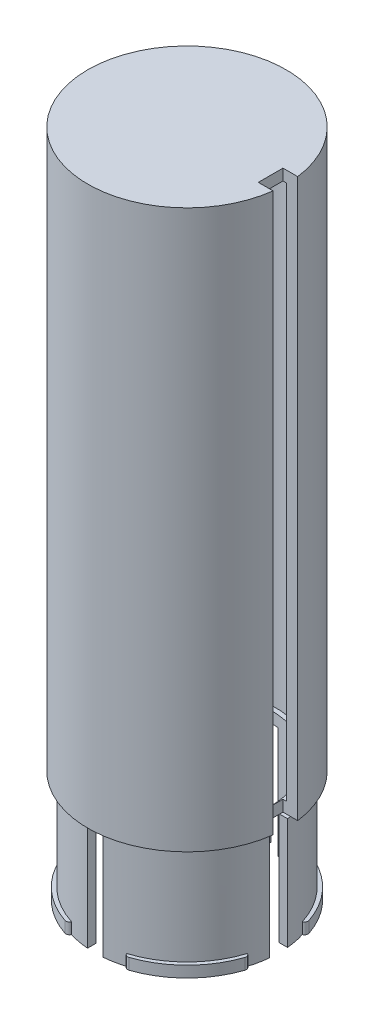
SolidWorks part; units mm, degrees
ref_plane "Front Plane" through (0, 0, 0) normal (0, 0, 1) x (1, 0, 0)
ref_plane "Top Plane" through (0, 0, 0) normal (0, 1, 0) x (1, 0, 0)
ref_plane "Right Plane" through (0, 0, 0) normal (1, 0, 0) x (0, 0, -1)
sketch "Sketch1" plane through (0, 0, 0) normal (0, 1, 0) x (1, 0, 0)
  line L5 (12.5724, 12.5724) -> (-12.5724, -12.5724) construction
  line L6 (12.5724, -12.5724) -> (-12.5724, 12.5724) construction
  circle A0 centre (0, 0) radius 17.78
  point P0 (0, 0)
  dimension "D1" = 35.56
extrude "Boss-Extrude1" add sketch "Sketch1" along normal blind 100
shell "Shell1" thickness 2
sketch "Sketch2" plane through (0, 0, 0) normal (1, 0, 0) x (0, 0, -1)
  line L0 (0, 19.558) -> (0, -19.558) construction
  line L1 (2.214, 104.2698) -> (-2.214, 104.2698)
  line L2 (2.214, 104.2698) -> (2.214, 0)
  line L3 (2.214, 0) -> (-2.214, 0)
  line L4 (-2.214, 104.2698) -> (-2.214, 0)
  line L5 (2.214, 104.2698) -> (-2.214, 0) construction
  line L6 (2.214, 0) -> (-2.214, 104.2698) construction
  line L7 (19.558, 0) -> (-19.558, 0) construction
  point P0 (0, 52.1349)
extrude "Cut-Extrude1" cut sketch "Sketch2" against normal mid plane 10 from offset 20
sketch "Sketch4" plane through (0, 0, 0) normal (0, -1, 0) x (1, 0, 0)
  circle A0 centre (0, 0) radius 16.51
extrude "Boss-Extrude2" add sketch "Sketch4" along normal blind 20
sketch "Sketch7" plane through (0, -20, 0) normal (0, -1, 0) x (-1, 0, 0)
  circle A0 centre (0, 0) radius 14.9532
extrude "Cut-Extrude4" cut sketch "Sketch7" against normal blind 32
sketch "Sketch8" plane through (0, 0, 0) normal (0, 1, 0) x (1, 0, 0)
  line L0 (0, -19.558) -> (0, 19.558) construction
  line L1 (-1.3929, 17.3486) -> (1.3929, 17.3486)
  line L2 (-1.3929, 17.3486) -> (-1.3929, 14.1994)
  line L3 (-1.3929, 14.1994) -> (1.3929, 14.1994)
  line L4 (1.3929, 17.3486) -> (1.3929, 14.1994)
  line L5 (-1.3929, 17.3486) -> (1.3929, 14.1994) construction
  line L6 (-1.3929, 14.1994) -> (1.3929, 17.3486) construction
  line L7 (14.2708, 1.6027) -> (17.42, 1.6027)
  line L8 (14.2708, 1.6027) -> (14.2708, -1.6027)
  line L9 (14.2708, -1.6027) -> (17.42, -1.6027)
  line L10 (17.42, 1.6027) -> (17.42, -1.6027)
  line L11 (14.2708, 1.6027) -> (17.42, -1.6027) construction
  line L12 (14.2708, -1.6027) -> (17.42, 1.6027) construction
  line L13 (-1.3929, -14.1994) -> (1.3929, -14.1994)
  line L14 (-1.3929, -14.1994) -> (-1.3929, -17.9109)
  line L15 (-1.3929, -17.9109) -> (1.3929, -17.9109)
  line L16 (1.3929, -14.1994) -> (1.3929, -17.9109)
  line L17 (-1.3929, -14.1994) -> (1.3929, -17.9109) construction
  line L18 (-1.3929, -17.9109) -> (1.3929, -14.1994) construction
  line L19 (-14.2708, 1.6027) -> (-17.42, 1.6027)
  line L20 (-17.42, 1.6027) -> (-17.42, -1.6027)
  line L21 (-14.2708, -1.6027) -> (-17.42, -1.6027)
  line L22 (-14.2708, 1.6027) -> (-14.2708, -1.6027)
  point P0 (0, 15.774)
  point P5 (15.8454, 0)
  point P10 (0, -16.0552)
extrude "Cut-Extrude5" cut sketch "Sketch8" against normal through all
sketch "Sketch9" plane through (0, -20, 0) normal (0, -1, 0) x (1, 0, 0)
  line L0 (19.558, 0) -> (-19.558, 0) construction
  line L2 (0, -19.558) -> (0, 19.558) construction
  arc A0 (5.5504, 15.5126) -> (15.517, 5.546) centre (0.4944, 0.49) cw construction
  arc A1 (16.1412, 5.756) -> (5.7604, 16.1368) centre (0.4944, 0.49) ccw
  arc A2 (14.8929, 5.3359) -> (5.3403, 14.8885) centre (0.4944, 0.49) ccw
  arc A3 (14.8929, 5.3359) -> (16.1412, 5.756) centre (15.517, 5.546) ccw
  arc A4 (5.7604, 16.1368) -> (5.3403, 14.8885) centre (5.5504, 15.5126) ccw
  arc A5 (5.5504, -15.5126) -> (15.517, -5.546) centre (0.4944, -0.49) ccw construction
  arc A6 (16.1412, -5.756) -> (5.7604, -16.1368) centre (0.4944, -0.49) cw
  arc A7 (14.8929, -5.3359) -> (5.3403, -14.8885) centre (0.4944, -0.49) cw
  arc A8 (14.8929, -5.3359) -> (16.1412, -5.756) centre (15.517, -5.546) cw
  arc A9 (5.7604, -16.1368) -> (5.3403, -14.8885) centre (5.5504, -15.5126) cw
  arc A10 (-5.5504, -15.5126) -> (-15.517, -5.546) centre (-0.4944, -0.49) cw construction
  arc A11 (-16.1412, -5.756) -> (-5.7604, -16.1368) centre (-0.4944, -0.49) ccw
  arc A12 (-14.8929, -5.3359) -> (-5.3403, -14.8885) centre (-0.4944, -0.49) ccw
  arc A13 (-14.8929, -5.3359) -> (-16.1412, -5.756) centre (-15.517, -5.546) ccw
  arc A14 (-5.7604, -16.1368) -> (-5.3403, -14.8885) centre (-5.5504, -15.5126) ccw
  arc A15 (-5.5504, 15.5126) -> (-15.517, 5.546) centre (-0.4944, 0.49) ccw construction
  arc A16 (-16.1412, 5.756) -> (-5.7604, 16.1368) centre (-0.4944, 0.49) cw
  arc A17 (-14.8929, 5.3359) -> (-5.3403, 14.8885) centre (-0.4944, 0.49) cw
  arc A18 (-14.8929, 5.3359) -> (-16.1412, 5.756) centre (-15.517, 5.546) cw
  arc A19 (-5.7604, 16.1368) -> (-5.3403, 14.8885) centre (-5.5504, 15.5126) cw
  point P3 (11.7025, 11.6981)
  point P15 (11.7025, -11.6981)
  point P23 (-11.7025, -11.6981)
  point P31 (-11.7025, 11.6981)
extrude "Boss-Extrude4" add sketch "Sketch9" against normal blind 2
